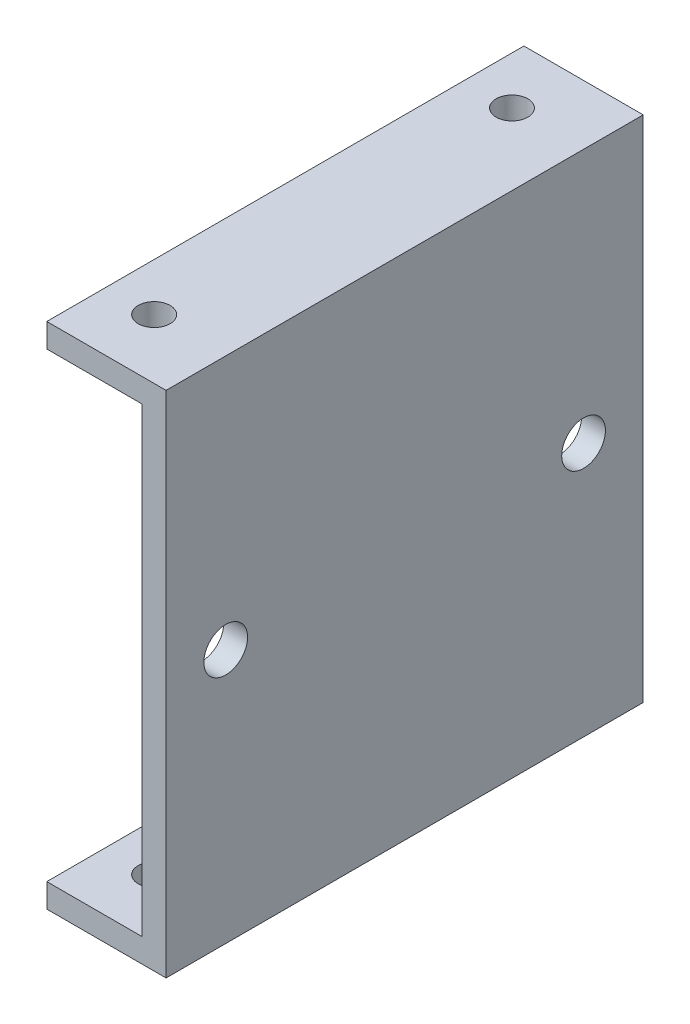
SolidWorks part; units mm, degrees
material "1060 合金"
ref_plane "前视基准面" through (0, 0, 0) normal (0, 0, 1) x (1, 0, 0)
ref_plane "上视基准面" through (0, 0, 0) normal (0, 1, 0) x (1, 0, 0)
ref_plane "右视基准面" through (0, 0, 0) normal (1, 0, 0) x (0, 0, -1)
sketch "草图1" plane through (0, 0, 0) normal (0, 0, 1) x (1, 0, 0)
  line L0 (0, 0) -> (15, 0)
  line L1 (15, 0) -> (15, -64)
  line L2 (15, -64) -> (0, -64)
  line L3 (0, -3) -> (12, -3)
  line L4 (12, -3) -> (12, -61)
  line L5 (12, -61) -> (0, -61)
  line L6 (0, 0) -> (0, -3)
  line L7 (0, -61) -> (0, -64)
  dimension "D1" = 64
  dimension "D2" = 15
  dimension "D3" = 3
extrude "凸台-拉伸1" add sketch "草图1" along normal mid plane 60
sketch "草图2" plane through (0, 0, 0) normal (0, 1, 0) x (1, 0, 0)
  line L0 (6, 22.5) -> (6, -22.5) construction
  line L3 (0, -30) -> (12, -30) construction
  line L4 (0, -30) -> (12, -30) construction
  circle A0 centre (6, 22.5) radius 2
  circle A1 centre (6, -22.5) radius 2
  point P4 (6, 0)
  point P5 (0, 0)
  point P12 (6, -30)
  point P13 (0, 0)
  dimension "D1" = 4
  dimension "D2" = 45
extrude "切除-拉伸1" cut sketch "草图2" against normal through all and the other way through all
sketch "草图3" plane through (15, 0, 0) normal (1, 0, 0) x (0, 0, -1)
  line L0 (-22.5, -32) -> (22.5, -32) construction
  line L1 (-30, -64) -> (-30, 0) construction
  circle A0 centre (-22.5, -32) radius 2.75
  circle A1 centre (22.5, -32) radius 2.75
  point P4 (0, -32)
  point P8 (-30, -32)
  dimension "D1" = 5.5
  dimension "D2" = 45
extrude "切除-拉伸2" cut sketch "草图3" against normal through all
